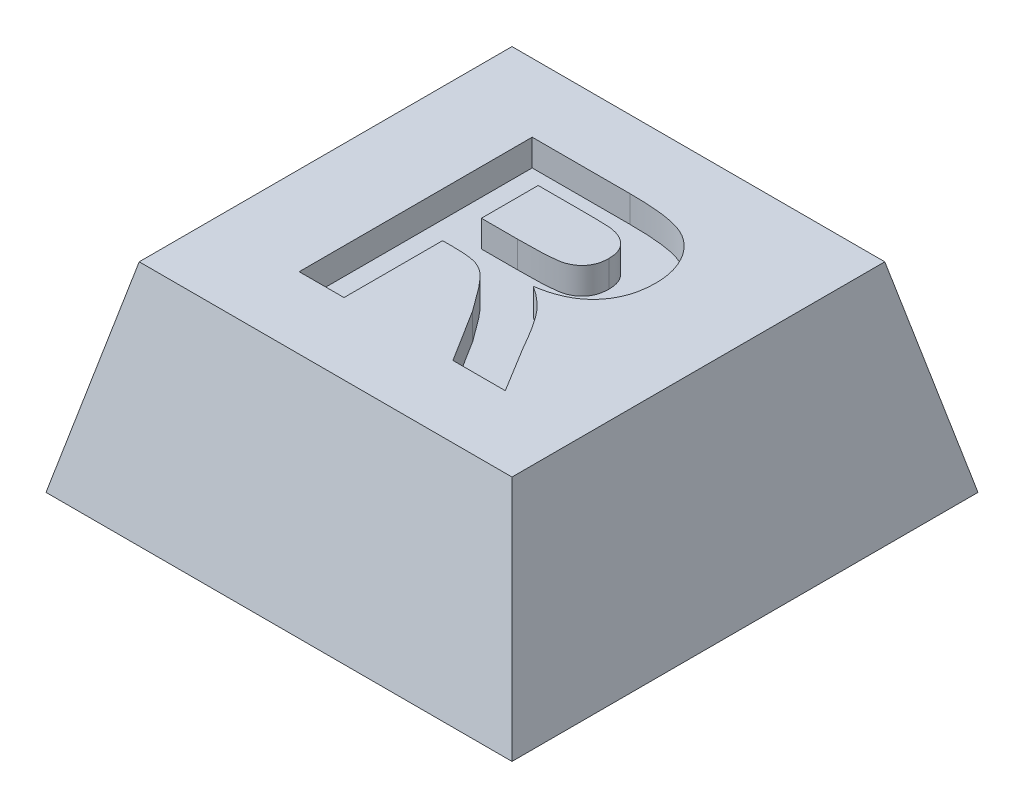
SolidWorks part; units mm, degrees
ref_plane "Front Plane" through (0, 0, 0) normal (0, 0, 1) x (1, 0, 0)
ref_plane "Top Plane" through (0, 0, 0) normal (0, 1, 0) x (1, 0, 0)
ref_plane "Right Plane" through (0, 0, 0) normal (1, 0, 0) x (0, 0, -1)
sketch "Sketch1" plane through (0, 0, 0) normal (0, 1, 0) x (1, 0, 0)
  line L1 (0, 0) -> (7, 0)
  line L2 (0, 0) -> (0, 7)
  line L3 (0, 7) -> (7, 7)
  line L4 (7, 0) -> (7, 7)
  dimension "D1" = 7
  dimension "D2" = 7
extrude "Boss-Extrude1" add sketch "Sketch1" along normal blind 3
sketch "Sketch2" plane through (0, 0, 0) normal (0, 0, 1) x (1, 0, 0)
  line L0 (0, 0) -> (0.7, 3)
  line L1 (0, 3) -> (7, 3) construction
  line L2 (0.7, 3) -> (0, 3)
  line L3 (0, 3) -> (0, 0)
  line L4 (7, 0) -> (6.3, 3)
  line L5 (6.3, 3) -> (7, 3)
  line L6 (7, 3) -> (7, 0)
  dimension "D1" = 0.7
  dimension "D2" = 0.7
extrude "Cut-Extrude1" cut sketch "Sketch2" against normal blind 7
sketch "Sketch3" plane through (0, 0, 0) normal (1, 0, 0) x (0, 0, -1)
  line L0 (0, 0) -> (0.7, 3)
  line L1 (7, 3) -> (0, 3) construction
  line L2 (0.7, 3) -> (0, 3)
  line L3 (0, 3) -> (0, 0)
  line L4 (7, 3) -> (6.3, 3)
  line L5 (6.3, 3) -> (7, 0)
  line L6 (7, 3) -> (7, 0)
  dimension "D1" = 0.7
  dimension "D2" = 0.7
extrude "Cut-Extrude2" cut sketch "Sketch3" along normal blind 11
sketch "Sketch4" plane through (0, 0, 0) normal (0, -1, 0) x (1, 0, 0)
  line L0 (3.5, 0) -> (3.5, -7) construction
  line L1 (0, 0) -> (7, 0) construction
  line L2 (7, -7) -> (0, -7) construction
  line L3 (0, -3.5) -> (7, -3.5) construction
  line L4 (0, -7) -> (0, 0) construction
  line L5 (7, 0) -> (7, -7) construction
  circle A0 centre (3.5, -3.5) radius 1.8
  dimension "D1" = 3.6
extrude "Cut-Extrude3" cut sketch "Sketch4" against normal blind 0.8
sketch "Sketch5" plane through (0, 3, 0) normal (0, 1, 0) x (1, 0, 0)
  text T0 "R" font "Arial" height 3.5
extrude "Cut-Extrude4" cut sketch "Sketch5" against normal blind 0.4
